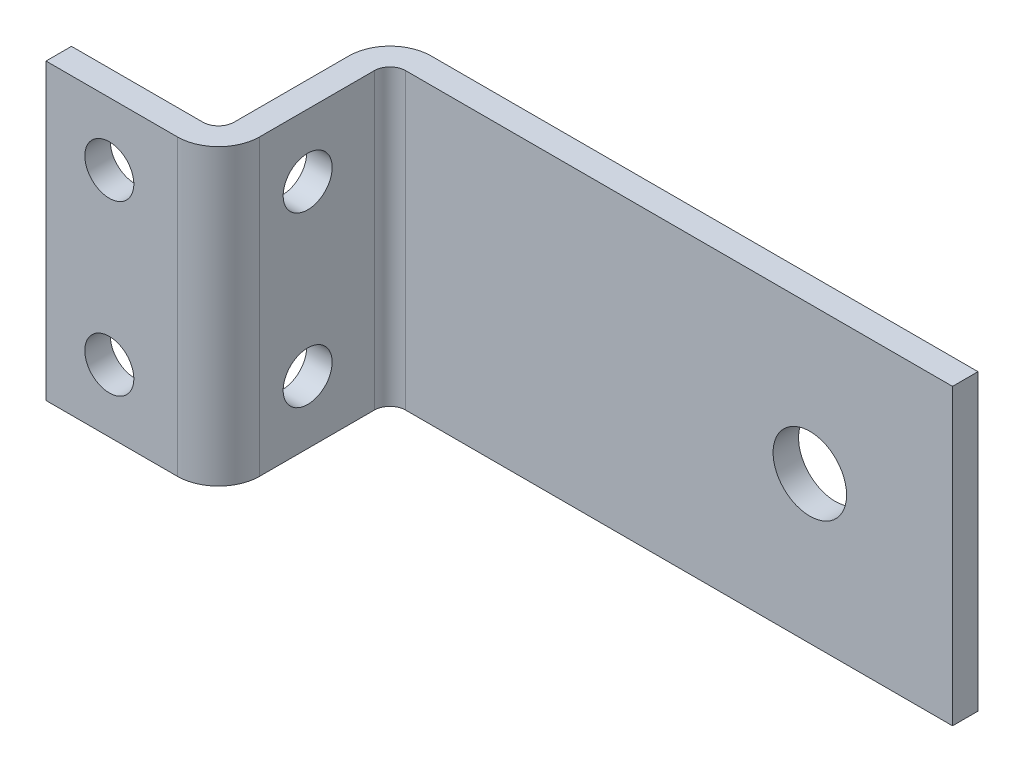
SolidWorks part; units mm, degrees
ref_plane "Front" through (0, 0, 0) normal (0, 0, 1) x (1, 0, 0)
ref_plane "Top" through (0, 0, 0) normal (0, 1, 0) x (1, 0, 0)
ref_plane "Right" through (0, 0, 0) normal (1, 0, 0) x (0, 0, -1)
sketch "Sketch1" plane through (0, 0, 0) normal (0, 1, 0) x (1, 0, 0)
  line L0 (0, -22.225) -> (0, 0)
  line L1 (0, 0) -> (76.2, 0)
  line L2 (0, -22.225) -> (-19.05, -22.225)
  dimension "A2" = 76.2
  dimension "A1" = 19.05
  dimension "Offset" = 22.225
extrude "Extrude-Thin1" add sketch "Sketch1" along normal mid plane 38.1 thin
sketch "Sketch4" plane through (-22.225, 0, 25.527) normal (0, 0, -1) x (-1, 0, 0)
  line L0 (-3.175, 19.05) -> (-3.175, -19.05) construction
  line L1 (-11.3792, 10.922) -> (-11.3792, -10.922) construction
  circle A0 centre (-11.3792, 10.922) radius 3.175
  circle A1 centre (-11.3792, -10.922) radius 3.175
  point P8 (-11.3792, 0)
extrude "Extrude3" cut sketch "Sketch4" along normal through all
sketch "Sketch9" plane through (3.302, 0, 0) normal (1, 0, 0) x (0, 0, -1)
  line L0 (-13.97, 10.922) -> (-13.97, -10.922) construction
  line L1 (-22.225, 10.922) -> (-25.527, 10.922) construction
  line L2 (-22.225, -10.922) -> (-25.527, -10.922) construction
  line L3 (0, 19.05) -> (0, -19.05) construction
  circle A0 centre (-13.97, 10.922) radius 3.175
  circle A1 centre (-13.97, -10.922) radius 3.175
  dimension "D1" = 6.35
extrude "Cut-Extrude3" cut sketch "Sketch9" against normal through all
sketch "Sketch8" plane through (0, 0, 3.302) normal (0, 0, 1) x (1, 0, 0)
  line L0 (-12.1412, 0) -> (57.7088, 0) construction
  line L1 (76.2, 19.05) -> (76.2, -19.05) construction
  circle A0 centre (57.7088, 0) radius 4.7625
  circle A1 centre (-12.1412, 0) radius 4.7625
  dimension "Hole Size" = 9.525
  dimension "Hole Offset H 2" = 69.85
  dimension "Hole Offset H 1" = 18.4912
extrude "Cut-Extrude2" cut sketch "Sketch8" against normal through all
sketch "Sketch10" plane through (0, 0, 0) normal (0, 1, 0) x (1, 0, 0)
  line L4 (3.302, -10.795) -> (0, -10.795) construction
  line L5 (0, -17.145) -> (3.302, -17.145) construction
  line L6 (3.302, -10.795) -> (0, -10.795)
  line L7 (0, -17.145) -> (3.302, -17.145)
  line L8 (-1.016, -13.97) -> (4.318, -13.97)
  line L9 (0, -13.97) -> (3.302, -13.97) construction
  line L10 (0, -20.193) -> (0, -5.334) construction
  point P8 (1.651, -10.795)
  point P9 (1.651, -13.97)
  dimension "D1" = 1.016
equation "\"D1@Sketch9\" = \"Hole Size@Sketch4\""
